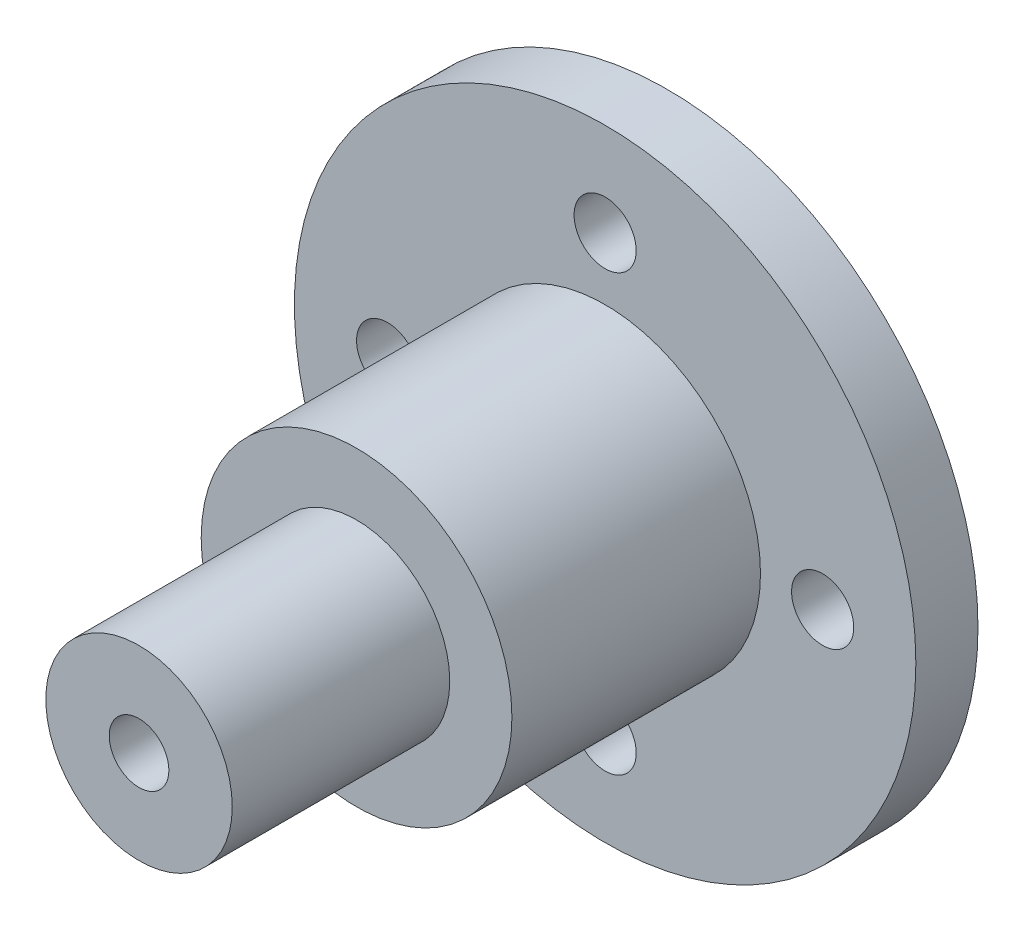
SolidWorks part; units mm, degrees
ref_plane "Front Plane" through (0, 0, 0) normal (0, 0, 1) x (1, 0, 0)
ref_plane "Top Plane" through (0, 0, 0) normal (0, 1, 0) x (1, 0, 0)
ref_plane "Right Plane" through (0, 0, 0) normal (1, 0, 0) x (0, 0, -1)
sketch "Sketch1" plane through (0, 0, 0) normal (0, 0, 1) x (1, 0, 0)
  circle A0 centre (0, 0) radius 10
  circle A1 centre (0, 0) radius 25
  circle A2 centre (0, 0) radius 17.5 construction
  circle A3 centre (0, 17.5) radius 2.5
  circle A4 centre (0, 0) radius 17.5 construction
  circle A5 centre (17.5, 0) radius 2.5
  circle A6 centre (0, 0) radius 17.5 construction
  circle A7 centre (0, -17.5) radius 2.5
  circle A8 centre (0, 0) radius 17.5 construction
  circle A9 centre (-17.5, 0) radius 2.5
  point P19 (0, 0)
  dimension "D1" = 35
  dimension "40" = 50
  dimension "D2" = 20
  dimension "D3" = 5
  dimension "D4" = 4
extrude "Boss-Extrude1" add sketch "Sketch1" along normal blind 5 contours A0 | A1 A9 A7 A5 A3 A0
sketch "Sketch2" plane through (0, 0, 5) normal (0, 0, 1) x (1, 0, 0)
  circle A0 centre (0, 0) radius 12.5
  dimension "D1" = 25
extrude "Boss-Extrude2" add sketch "Sketch2" along normal blind 20
sketch "Sketch3" plane through (0, 0, 25) normal (0, 0, 1) x (1, 0, 0)
  circle A0 centre (0, 0) radius 7.5
  dimension "D1" = 15
extrude "Boss-Extrude3" add sketch "Sketch3" along normal blind 17.5
sketch "Sketch4" plane through (0, 0, 42.5) normal (0, 0, 1) x (1, 0, 0)
  circle A0 centre (0, 0) radius 2.4
  dimension "D1" = 4.8
extrude "Cut-Extrude1" cut sketch "Sketch4" against normal blind 10
